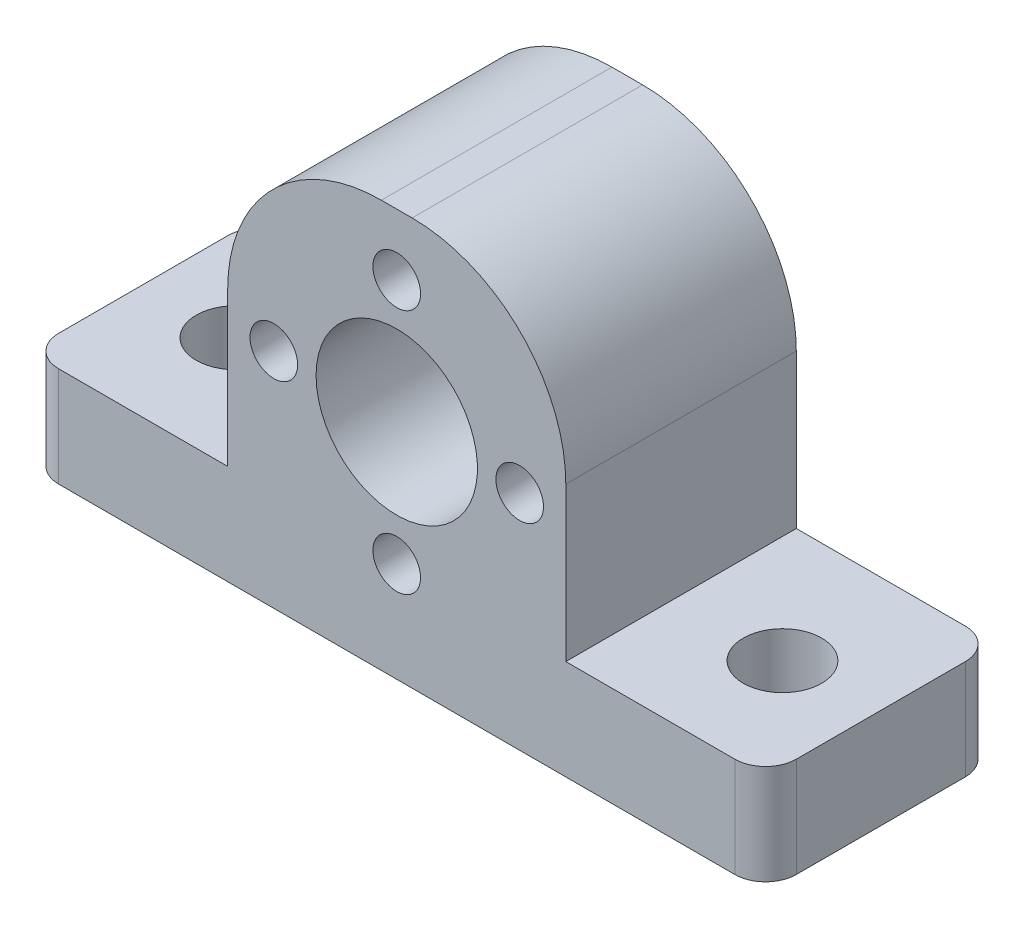
SolidWorks part; units mm, degrees
ref_plane "前视基准面" through (0, 0, 0) normal (0, 0, 1) x (1, 0, 0)
ref_plane "上视基准面" through (0, 0, 0) normal (0, 1, 0) x (1, 0, 0)
ref_plane "右视基准面" through (0, 0, 0) normal (1, 0, 0) x (0, 0, -1)
sketch "草图1" plane through (0, 0, 0) normal (0, 1, 0) x (1, 0, 0)
  line L1 (-25.9485, 7.8987) -> (22.0515, 7.8987)
  line L2 (-25.9485, 7.8987) -> (-25.9485, -7.1013)
  line L3 (-25.9485, -7.1013) -> (22.0515, -7.1013)
  line L4 (22.0515, 7.8987) -> (22.0515, -7.1013)
  dimension "D1" = 15
  dimension "D2" = 48
extrude "凸台-拉伸1" add sketch "草图1" along normal blind 6.5
sketch "草图2" plane through (0, 6.5, 0) normal (0, 1, 0) x (1, 0, 0)
  line L0 (22.0515, 7.8987) -> (-25.9485, 7.8987) construction
  line L1 (-12.9485, 7.8987) -> (9.0515, 7.8987)
  line L2 (-12.9485, 7.8987) -> (-12.9485, -7.1013)
  line L3 (-12.9485, -7.1013) -> (9.0515, -7.1013)
  line L4 (9.0515, 7.8987) -> (9.0515, -7.1013)
  line L5 (-25.9485, -7.1013) -> (22.0515, -7.1013) construction
  line L6 (22.0515, -7.1013) -> (22.0515, 7.8987) construction
  dimension "D1" = 22
  dimension "D2" = 13
extrude "凸台-拉伸2" add sketch "草图2" along normal blind 20
fillet "圆角1" radius 10 2 edges at (9.0515, 26.5, -0.3987) (-12.9485, 26.5, -0.3987)
sketch "草图3" plane through (0, 6.5, 0) normal (0, 1, 0) x (1, 0, 0)
  line L0 (-25.9485, 7.8987) -> (-25.9485, -7.1013) construction
  line L1 (22.0515, -7.1013) -> (22.0515, 7.8987) construction
  circle A0 centre (-19.9485, 0.3987) radius 2.55
  circle A1 centre (16.0515, 0) radius 2.55
  dimension "D1" = 5.1
  dimension "D2" = 6
  dimension "D3" = 6
  dimension "D4" = 5.1
extrude "切除-拉伸1" cut sketch "草图3" against normal through all
sketch "草图4" plane through (0, 0, -7.8987) normal (0, 0, -1) x (-1, 0, 0)
  line L0 (2.9485, 26.5) -> (0.9485, 26.5) construction
  line L2 (12.9485, 16.5) -> (12.9485, 6.5) construction
  circle A0 centre (1.9485, 14.5) radius 5.25
  circle A1 centre (1.9485, 14.5) radius 8 construction
  circle A2 centre (1.9485, 22.5) radius 1.55
  circle A3 centre (9.9485, 14.5) radius 1.55
  circle A4 centre (1.9485, 6.5) radius 1.55
  circle A5 centre (-6.0515, 14.5) radius 1.55
  dimension "D1" = 12
  dimension "D2" = 16
  dimension "D3" = 10.5
  dimension "D4" = 3.1
  dimension "D5" = 11
extrude "切除-拉伸2" cut sketch "草图4" against normal blind 20
fillet "圆角2" radius 2 4 edges at (22.0515, 3.25, -7.8987) (22.0515, 3.25, 7.1013) (-25.9485, 3.25, -7.8987) (-25.9485, 3.25, 7.1013)
